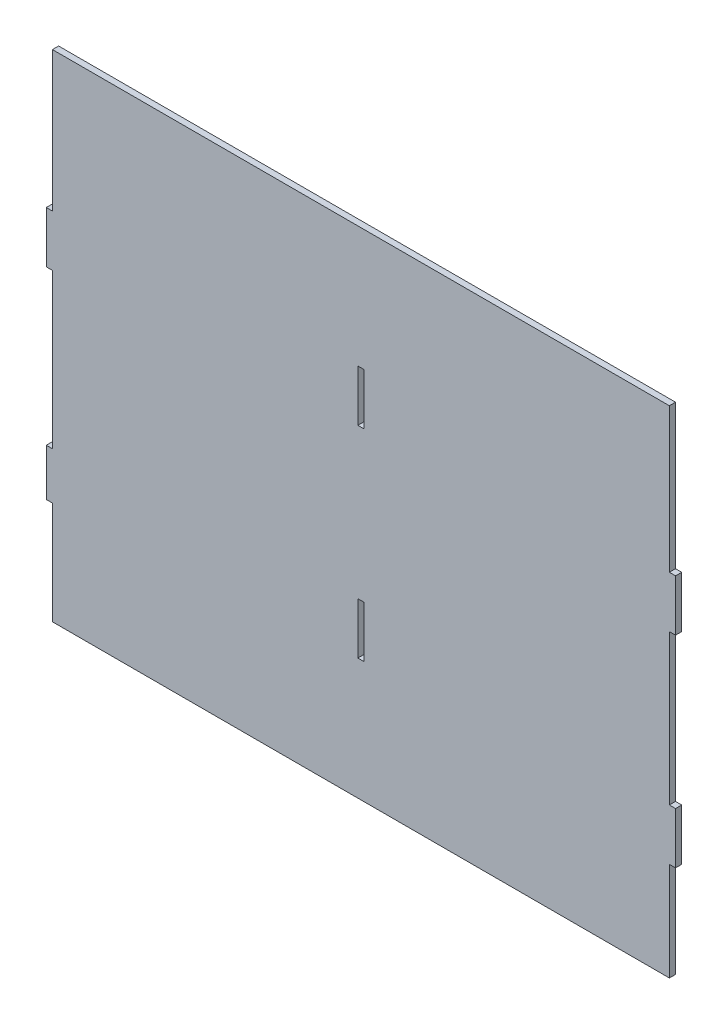
SolidWorks part; units mm, degrees
material "Maple"
ref_plane "Front Plane" through (0, 0, 0) normal (0, 0, 1) x (1, 0, 0)
ref_plane "Top Plane" through (0, 0, 0) normal (0, 1, 0) x (1, 0, 0)
ref_plane "Right Plane" through (0, 0, 0) normal (1, 0, 0) x (0, 0, -1)
sketch "Sketch1" plane through (0, 0, 0) normal (0, 0, 1) x (1, 0, 0)
  line L1 (-300, 241) -> (300, 241)
  line L2 (-300, 241) -> (-300, 105)
  line L3 (-300, -241) -> (300, -241)
  line L4 (300, 241) -> (300, 100.7323)
  line L5 (-300, 241) -> (300, -241) construction
  line L6 (-300, -241) -> (300, 241) construction
  line L7 (-306, 105) -> (-300, 105)
  line L8 (-306, 105) -> (-306, 55)
  line L9 (-306, 55) -> (-300, 55)
  line L11 (-300, 198) -> (-282.5, 173) construction
  line L12 (-300, -141) -> (-300, -241)
  line L13 (0, 98) -> (0, 241) construction
  line L14 (306, 50.7323) -> (300, 50.7323)
  line L15 (306, 100.7323) -> (306, 50.7323)
  line L16 (306, 100.7323) -> (300, 100.7323)
  line L20 (-306, -95.2677) -> (-300, -95.2677)
  line L22 (-306, -141) -> (-300, -141)
  line L23 (-306, -141) -> (-306, -95.2677)
  line L24 (-300, 55) -> (-300, -95.2677)
  line L27 (-3, 123) -> (3, 123)
  line L28 (-3, 123) -> (-3, 73)
  line L29 (-3, 73) -> (3, 73)
  line L30 (3, 123) -> (3, 73)
  line L31 (-3, 123) -> (3, 73) construction
  line L32 (-3, 73) -> (3, 123) construction
  line L39 (300, 50.7323) -> (300, -95.2677)
  line L40 (0, 98) -> (0, -241) construction
  line L41 (306, -145.2677) -> (300, -145.2677)
  line L42 (306, -145.2677) -> (306, -95.2677)
  line L43 (306, -95.2677) -> (300, -95.2677)
  line L44 (300, -145.2677) -> (300, -241)
  line L45 (0, 0) -> (300, 0) construction
  line L46 (-3, -73) -> (3, -73)
  line L47 (3, -123) -> (3, -73)
  line L48 (-3, -123) -> (3, -123)
  line L49 (-3, -123) -> (-3, -73)
  point P0 (0, 0)
  point P6 (-300, 198)
  point P12 (0, 98)
  point P31 (-156.1598, -207)
  dimension "D1" = 600
  dimension "D2" = 482
  dimension "D3" = 136
  dimension "D4" = 6
  dimension "D5" = 50
  dimension "D6" = 50
  dimension "D7" = 100
  dimension "D8" = 118
  dimension "D9" = 6
  dimension "D10" = 6
  dimension "D11" = 6
  dimension "D12" = 6
extrude "Boss-Extrude1" add sketch "Sketch1" along normal blind 6
